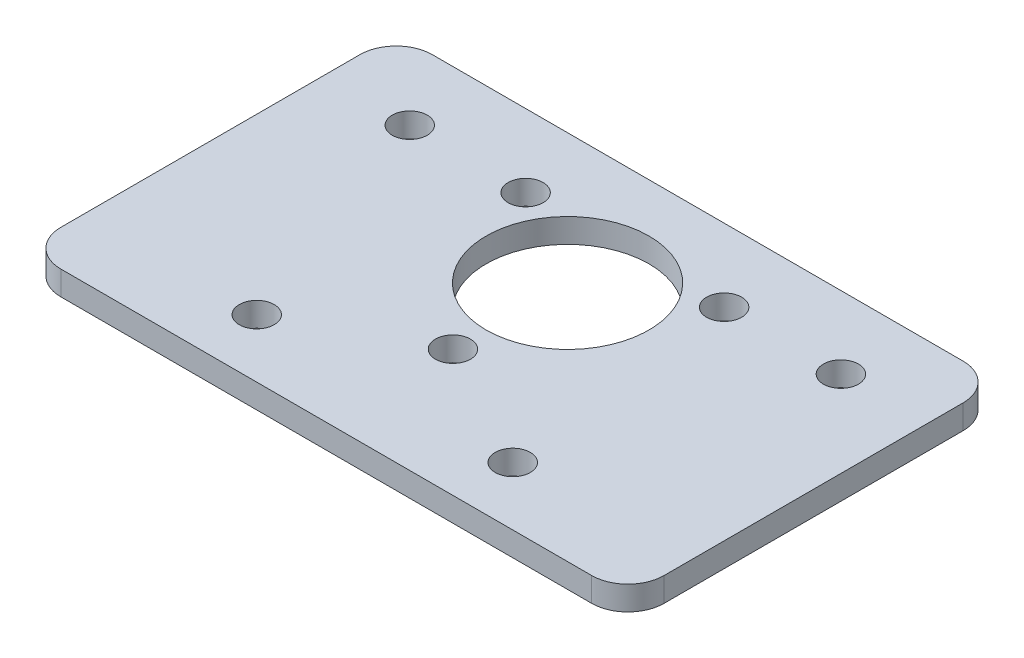
SolidWorks part; units mm, degrees
material "Thornel Mat VMA"
ref_plane "前视基准面" through (0, 0, 0) normal (0, 0, 1) x (1, 0, 0)
ref_plane "上视基准面" through (0, 0, 0) normal (0, 1, 0) x (1, 0, 0)
ref_plane "右视基准面" through (0, 0, 0) normal (1, 0, 0) x (0, 0, -1)
other "Configuration Table"
sketch "草图2" plane through (0, 0, 0) normal (0, 1, 0) x (1, 0, 0)
  line L0 (0, 18.0653) -> (0, -25.3249) construction
  line L1 (-25, 20.6159) -> (25, 20.6159) construction
  line L2 (-25, 20.6159) -> (-25, -20) construction
  line L3 (-25, -20) -> (25, -20)
  line L4 (25, 20.6159) -> (25, -20) construction
  line L5 (-30.1833, 0) -> (36.8845, 0) construction
  line L6 (-8.2272, 4.75) -> (0, 0) construction
  line L7 (-10.6112, -15.1543) -> (0, 0) construction
  line L8 (0, 0) -> (-17.8696, 4.7882) construction
  line L9 (-25, -20) -> (-25, 10.7882)
  line L10 (-25, 10.7882) -> (25, 10.7882)
  line L11 (25, 10.7882) -> (25, -20)
  circle A0 centre (0, 0) radius 6.75
  circle A1 centre (0, 0) radius 9.5 construction
  circle A2 centre (-8.2272, 4.75) radius 1.45
  circle A3 centre (0, -9.5) radius 1.45
  circle A4 centre (8.2272, 4.75) radius 1.45
  circle A5 centre (0, 0) radius 18.5 construction
  circle A6 centre (-10.6112, -15.1543) radius 1.45
  circle A7 centre (-17.8696, 4.7882) radius 1.45
  circle A8 centre (10.6112, -15.1543) radius 1.45
  circle A9 centre (17.8696, 4.7882) radius 1.45
  dimension "D1" = 13.5
  dimension "D2" = 19
  dimension "D4" = 2.9
  dimension "D5" = 37
  dimension "D8" = 6
  dimension "D3" = 120
  dimension "D6" = 35
  dimension "D7" = 70
  dimension "D9" = 20
  dimension "D10" = 50
extrude "凸台-拉伸1" add sketch "草图2" along normal blind 2
fillet "圆角2" radius 3 4 edges at (-25, 1, 20) (-25, 1, -10.7882) (25, 1, 20) (25, 1, -10.7882)
